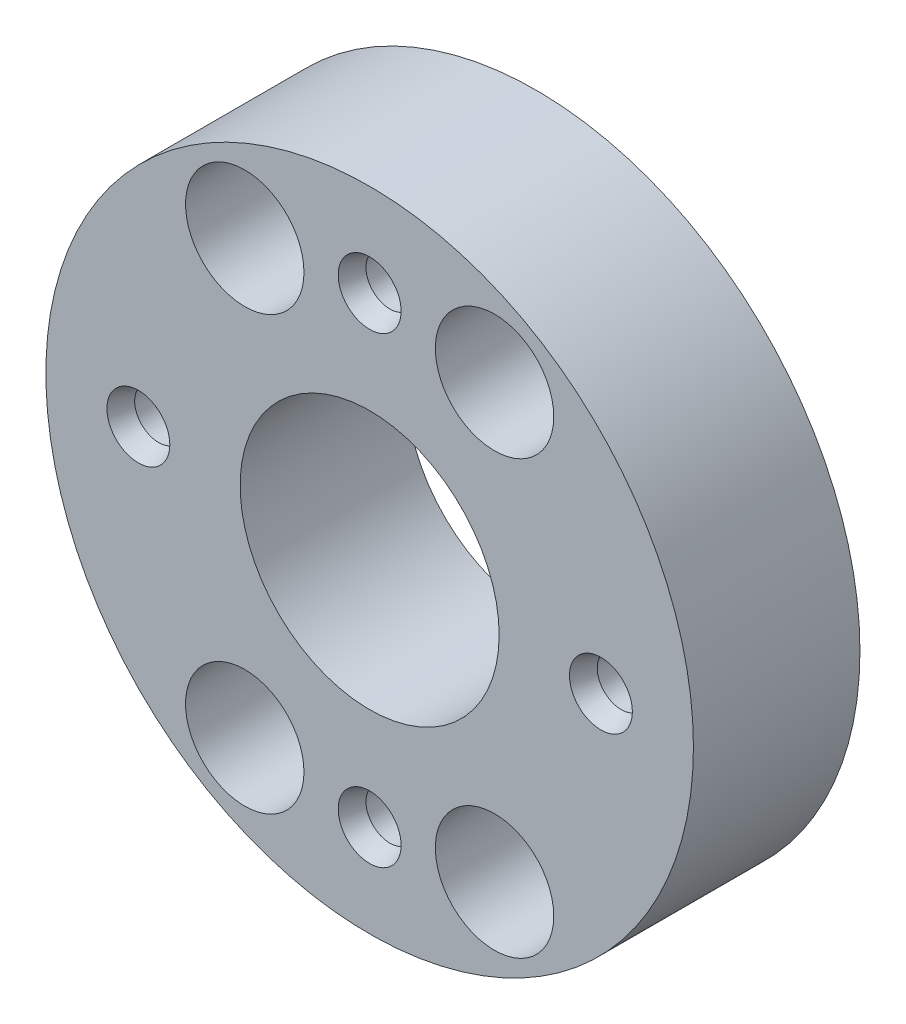
SolidWorks part; units mm, degrees
ref_plane "前视基准面" through (0, 0, 0) normal (0, 0, 1) x (1, 0, 0)
ref_plane "上视基准面" through (0, 0, 0) normal (0, 1, 0) x (1, 0, 0)
ref_plane "右视基准面" through (0, 0, 0) normal (1, 0, 0) x (0, 0, -1)
other "Configuration Table"
sketch "草图1" plane through (0, 0, 0) normal (0, 0, 1) x (1, 0, 0)
  circle A0 centre (0, 0) radius 17.5
extrude "凸台-拉伸1" add sketch "草图1" against normal blind 9
sketch "草图2" plane through (0, 0, 0) normal (0, 0, 1) x (1, 0, 0)
  circle A0 centre (12.5, 0) radius 1.3
  circle A1 centre (0, -12.5) radius 1.3
  circle A2 centre (-12.5, 0) radius 1.3
  circle A3 centre (0, 12.5) radius 1.3
  point P11 (0, 0)
  dimension "D1" = 4
extrude "切除-拉伸1" cut sketch "草图2" against normal blind 8
sketch "草图3" plane through (0, 0, 0) normal (0, 0, 1) x (1, 0, 0)
  circle A1 centre (6.75, -11.6913) radius 1.65
  circle A2 centre (-6.75, -11.6913) radius 1.65
  circle A4 centre (-6.75, 11.6913) radius 1.65
  circle A5 centre (6.75, 11.6913) radius 1.65
  point P14 (0, 0)
extrude "切除-拉伸2" cut sketch "草图3" against normal up to surface (9 mm away) up to face at (17.5, 0, -9)
sketch "草图4" plane through (0, 0, 0) normal (0, 0, 1) x (1, 0, 0)
  circle A0 centre (0, 0) radius 7
extrude "切除-拉伸3" cut sketch "草图4" against normal up to surface (9 mm away) up to face at (8.4, 11.6913, -9)
chamfer "倒角1" distance 0.4 angle 70 4 edges at (-11.2, 0, 0) (1.3, -12.5, 0) (13.8, 0, 0) (1.3, 12.5, 0)
sketch "草图5" plane through (0, 0, 0) normal (0, 0, 1) x (1, 0, 0)
  circle A0 centre (-6.75, 11.6913) radius 3.2
  circle A1 centre (6.75, 11.6913) radius 3.2
  circle A2 centre (6.75, -11.6913) radius 3.2
  circle A3 centre (-6.75, -11.6913) radius 3.2
extrude "切除-拉伸4" cut sketch "草图5" against normal offset from surface (5 mm away) 4 up to face at (7, 0, -9)
